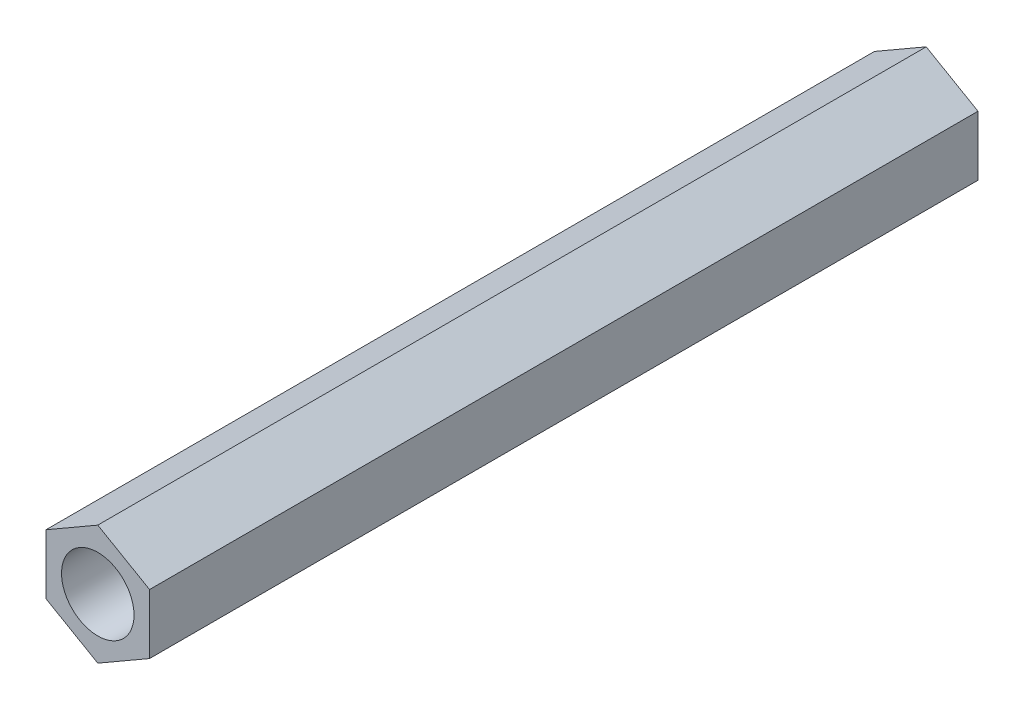
SolidWorks part; units mm, degrees
ref_plane "前基準面" through (0, 0, 0) normal (0, 0, 1) x (1, 0, 0)
ref_plane "上基準面" through (0, 0, 0) normal (0, 1, 0) x (1, 0, 0)
ref_plane "右基準面" through (0, 0, 0) normal (1, 0, 0) x (0, 0, -1)
sketch "草圖1" plane through (0, 0, 0) normal (0, 0, 1) x (1, 0, 0)
  line L1 (0, -2.8868) -> (2.5, -1.4434)
  line L2 (2.5, -1.4434) -> (2.5, 1.4434)
  line L3 (2.5, 1.4434) -> (0, 2.8868)
  line L4 (0, 2.8868) -> (-2.5, 1.4434)
  line L5 (-2.5, 1.4434) -> (-2.5, -1.4434)
  line L6 (-2.5, -1.4434) -> (0, -2.8868)
  circle A0 centre (0, 0) radius 2.5 construction
  dimension "D1" = 5
extrude "填料-伸長1" add sketch "草圖1" along normal blind 40
sketch "草圖2" plane through (0, 0, 40) normal (0, 0, 1) x (1, 0, 0)
  circle A0 centre (0, 0) radius 1.75
  dimension "D1" = 3.5
extrude "除料-伸長1" cut sketch "草圖2" against normal through all both and the other way through all
